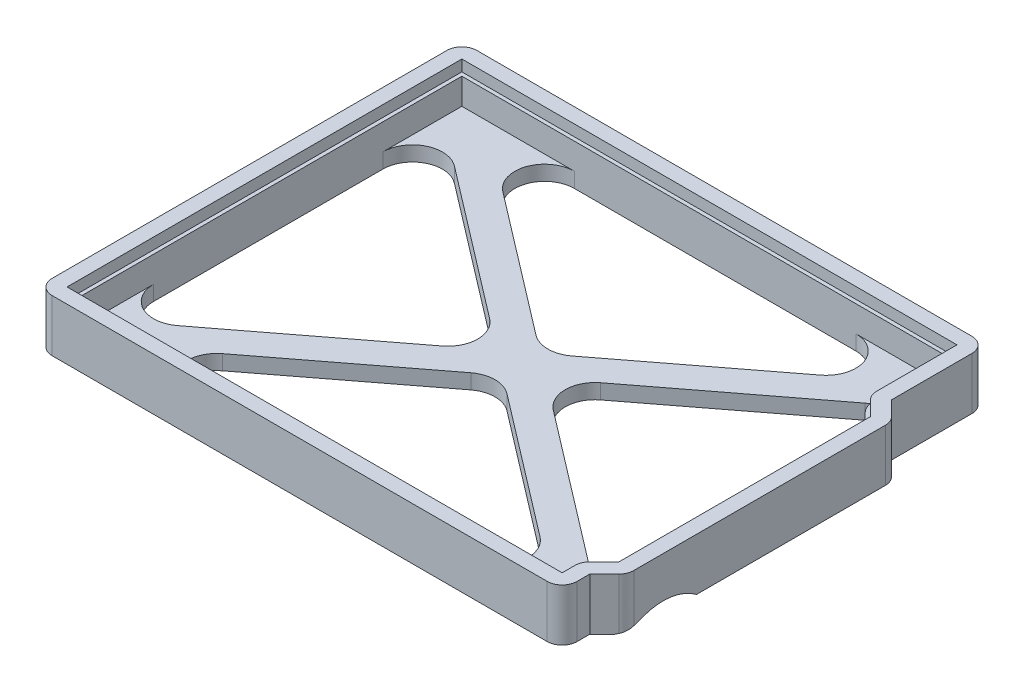
SolidWorks part; units mm, degrees
ref_plane "Спереди" through (0, 0, 0) normal (0, 0, 1) x (1, 0, 0)
ref_plane "Сверху" through (0, 0, 0) normal (0, 1, 0) x (1, 0, 0)
ref_plane "Справа" through (0, 0, 0) normal (1, 0, 0) x (0, 0, -1)
sketch "Эскиз1" plane through (0, 0, 0) normal (0, 1, 0) x (1, 0, 0)
  line L1 (-34.5, -26.5) -> (31.96, -26.5)
  line L2 (-34.5, -26.5) -> (-34.5, 26.5)
  line L3 (-34.5, 26.5) -> (31.96, 26.5)
  line L4 (34.5, -21.42) -> (34.5, 12.346)
  line L10 (-34, -26) -> (-34, 26)
  line L11 (31.96, 14.886) -> (31.96, 26.5)
  line L13 (-36.5, -28.5) -> (33.96, -28.5)
  line L14 (-36.5, -28.5) -> (-36.5, 28.5)
  line L17 (-21.3217, 18.8226) -> (-2.4298, 4.3758)
  line L21 (21.3217, -18.8226) -> (2.4298, -4.3758)
  line L25 (-21.3217, -18.8226) -> (-2.4298, -4.3758)
  line L29 (21.3217, 18.8226) -> (2.4298, 4.3758)
  line L30 (-7.4476, -3.1774) -> (-27.5702, -18.5653)
  line L31 (-7.4476, 3.1774) -> (-27.5702, 18.5653)
  line L32 (7.4476, -3.1774) -> (27.5702, -18.5653)
  line L33 (7.4476, 3.1774) -> (27.5702, 18.5653)
  line L34 (31.96, 14.886) -> (34.5, 12.346)
  line L36 (31.96, -23.96) -> (34.5, -21.42)
  line L37 (31.96, -23.96) -> (31.96, -26.5)
  line L40 (31.46, 14.886) -> (31.46, 26)
  line L41 (31.96, 28.5) -> (33.96, 28.5)
  line L42 (31.6064, 14.5324) -> (34, 12.1389)
  line L43 (31.6064, 14.5324) -> (31.46, 14.6789)
  line L44 (31.46, 14.6789) -> (31.46, 14.886)
  line L45 (31.46, -26) -> (-34, -26)
  line L46 (31.46, -23.96) -> (31.46, -26)
  line L47 (34, -21.2129) -> (34, 12.1389)
  line L48 (31.6064, -23.6064) -> (34, -21.2129)
  line L49 (31.6064, -23.6064) -> (31.46, -23.7529)
  line L50 (31.46, -23.7529) -> (31.46, -23.96)
  line L51 (31.46, 26) -> (-34, 26)
  line L52 (33.96, 28.5) -> (33.96, 15.7144)
  line L53 (31.96, 28.5) -> (-36.5, 28.5)
  line L54 (33.96, 15.7144) -> (36.5, 13.1744)
  line L55 (36.5, 13.1744) -> (36.5, -22.2484)
  line L57 (33.96, -26.5) -> (33.96, -24.7884)
  line L59 (33.96, -24.7884) -> (36.5, -22.2484)
  line L60 (33.96, -26.5) -> (33.96, -28.5)
  arc A0 (-27.5702, 18.5653) -> (-34, 15.3879) centre (-30, 15.3879) ccw
  arc A1 (-7.4476, -3.1774) -> (-7.4476, 3.1774) centre (-9.8774, 0) ccw
  arc A2 (-34, -15.3879) -> (-27.5702, -18.5653) centre (-30, -15.3879) ccw
  arc A3 (-21.3217, -18.8226) -> (-18.8919, -26) centre (-18.8919, -22) ccw
  arc A4 (18.8919, -26) -> (21.3217, -18.8226) centre (18.8919, -22) ccw
  arc A5 (2.4298, -4.3758) -> (-2.4298, -4.3758) centre (0, -7.5533) ccw
  arc A6 (7.4476, 3.1774) -> (7.4476, -3.1774) centre (9.8774, 0) ccw
  arc A7 (27.5702, -18.5653) -> (34, -15.3879) centre (30, -15.3879) ccw
  arc A8 (31.46, 19.1119) -> (27.5702, 18.5653) centre (30, 15.3879) ccw
  arc A9 (21.3217, 18.8226) -> (18.8919, 26) centre (18.8919, 22) ccw
  arc A10 (-18.8919, 26) -> (-21.3217, 18.8226) centre (-18.8919, 22) ccw
  arc A11 (-2.4298, 4.3758) -> (2.4298, 4.3758) centre (0, 7.5533) ccw
  point P0 (0, 0)
  point P6 (0, 0)
  point P11 (0, 0)
extrude "Бобышка-Вытянуть1" add sketch "Эскиз1" along normal blind 2
sketch "Эскиз5" plane through (0, 0, 0) normal (0, 1, 0) x (1, 0, 0)
  line L1 (-34.5, -26.5) -> (31.96, -26.5)
  line L2 (-34.5, -26.5) -> (-34.5, 26.5)
  line L3 (-34.5, 26.5) -> (31.96, 26.5)
  line L4 (34.5, -21.42) -> (34.5, 12.346)
  line L10 (-34, -26) -> (-34, 26)
  line L11 (31.96, 14.886) -> (31.96, 26.5)
  line L13 (-36.5, -28.5) -> (33.96, -28.5)
  line L14 (-36.5, -28.5) -> (-36.5, 28.5)
  line L17 (-21.3217, 18.8226) -> (-2.4298, 4.3758)
  line L21 (21.3217, -18.8226) -> (2.4298, -4.3758)
  line L25 (-21.3217, -18.8226) -> (-2.4298, -4.3758)
  line L29 (21.3217, 18.8226) -> (2.4298, 4.3758)
  line L30 (-7.4476, -3.1774) -> (-27.5702, -18.5653)
  line L31 (-7.4476, 3.1774) -> (-27.5702, 18.5653)
  line L32 (7.4476, -3.1774) -> (27.5702, -18.5653)
  line L33 (7.4476, 3.1774) -> (27.5702, 18.5653)
  line L34 (31.96, 14.886) -> (34.5, 12.346)
  line L36 (31.96, -23.96) -> (34.5, -21.42)
  line L37 (31.96, -23.96) -> (31.96, -26.5)
  line L40 (31.46, 14.886) -> (31.46, 26)
  line L41 (31.96, 28.5) -> (33.96, 28.5)
  line L42 (31.6064, 14.5324) -> (34, 12.1389)
  line L43 (31.6064, 14.5324) -> (31.46, 14.6789)
  line L44 (31.46, 14.6789) -> (31.46, 14.886)
  line L45 (31.46, -26) -> (-34, -26)
  line L46 (31.46, -23.96) -> (31.46, -26)
  line L47 (34, -21.2129) -> (34, 12.1389)
  line L48 (31.6064, -23.6064) -> (34, -21.2129)
  line L49 (31.6064, -23.6064) -> (31.46, -23.7529)
  line L50 (31.46, -23.7529) -> (31.46, -23.96)
  line L51 (31.46, 26) -> (-34, 26)
  line L52 (33.96, 28.5) -> (33.96, 15.7144)
  line L53 (31.96, 28.5) -> (-36.5, 28.5)
  line L54 (33.96, 15.7144) -> (36.5, 13.1744)
  line L55 (36.5, 13.1744) -> (36.5, -22.2484)
  line L57 (33.96, -26.5) -> (33.96, -24.7884)
  line L59 (33.96, -24.7884) -> (36.5, -22.2484)
  line L60 (33.96, -26.5) -> (33.96, -28.5)
  arc A0 (-27.5702, 18.5653) -> (-34, 15.3879) centre (-30, 15.3879) ccw
  arc A1 (-7.4476, -3.1774) -> (-7.4476, 3.1774) centre (-9.8774, 0) ccw
  arc A2 (-34, -15.3879) -> (-27.5702, -18.5653) centre (-30, -15.3879) ccw
  arc A3 (-21.3217, -18.8226) -> (-18.8919, -26) centre (-18.8919, -22) ccw
  arc A4 (18.8919, -26) -> (21.3217, -18.8226) centre (18.8919, -22) ccw
  arc A5 (2.4298, -4.3758) -> (-2.4298, -4.3758) centre (0, -7.5533) ccw
  arc A6 (7.4476, 3.1774) -> (7.4476, -3.1774) centre (9.8774, 0) ccw
  arc A7 (27.5702, -18.5653) -> (34, -15.3879) centre (30, -15.3879) ccw
  arc A8 (31.46, 19.1119) -> (27.5702, 18.5653) centre (30, 15.3879) ccw
  arc A9 (21.3217, 18.8226) -> (18.8919, 26) centre (18.8919, 22) ccw
  arc A10 (-18.8919, 26) -> (-21.3217, 18.8226) centre (-18.8919, 22) ccw
  arc A11 (-2.4298, 4.3758) -> (2.4298, 4.3758) centre (0, 7.5533) ccw
  point P0 (0, 0)
  point P6 (0, 0)
  point P11 (0, 0)
sketch "Эскиз6" plane through (0, 0, 0) normal (0, 1, 0) x (1, 0, 0)
  line L1 (-34.5, -26.5) -> (31.96, -26.5)
  line L2 (-34.5, -26.5) -> (-34.5, 26.5)
  line L3 (-34.5, 26.5) -> (31.96, 26.5)
  line L4 (34.5, -21.42) -> (34.5, 12.346)
  line L10 (-34, -26) -> (-34, 26)
  line L11 (31.96, 14.886) -> (31.96, 26.5)
  line L13 (-36.5, -28.5) -> (33.96, -28.5)
  line L14 (-36.5, -28.5) -> (-36.5, 28.5)
  line L17 (-21.3217, 18.8226) -> (-2.4298, 4.3758)
  line L21 (21.3217, -18.8226) -> (2.4298, -4.3758)
  line L25 (-21.3217, -18.8226) -> (-2.4298, -4.3758)
  line L29 (21.3217, 18.8226) -> (2.4298, 4.3758)
  line L30 (-7.4476, -3.1774) -> (-27.5702, -18.5653)
  line L31 (-7.4476, 3.1774) -> (-27.5702, 18.5653)
  line L32 (7.4476, -3.1774) -> (27.5702, -18.5653)
  line L33 (7.4476, 3.1774) -> (27.5702, 18.5653)
  line L34 (31.96, 14.886) -> (34.5, 12.346)
  line L36 (31.96, -23.96) -> (34.5, -21.42)
  line L37 (31.96, -23.96) -> (31.96, -26.5)
  line L40 (31.46, 14.886) -> (31.46, 26)
  line L41 (31.96, 28.5) -> (33.96, 28.5)
  line L42 (31.6064, 14.5324) -> (34, 12.1389)
  line L43 (31.6064, 14.5324) -> (31.46, 14.6789)
  line L44 (31.46, 14.6789) -> (31.46, 14.886)
  line L45 (31.46, -26) -> (-34, -26)
  line L46 (31.46, -23.96) -> (31.46, -26)
  line L47 (34, -21.2129) -> (34, 12.1389)
  line L48 (31.6064, -23.6064) -> (34, -21.2129)
  line L49 (31.6064, -23.6064) -> (31.46, -23.7529)
  line L50 (31.46, -23.7529) -> (31.46, -23.96)
  line L51 (31.46, 26) -> (-34, 26)
  line L52 (33.96, 28.5) -> (33.96, 15.7144)
  line L53 (31.96, 28.5) -> (-36.5, 28.5)
  line L54 (33.96, 15.7144) -> (36.5, 13.1744)
  line L55 (36.5, 13.1744) -> (36.5, -22.2484)
  line L57 (33.96, -26.5) -> (33.96, -24.7884)
  line L59 (33.96, -24.7884) -> (36.5, -22.2484)
  line L60 (33.96, -26.5) -> (33.96, -28.5)
  arc A0 (-27.5702, 18.5653) -> (-34, 15.3879) centre (-30, 15.3879) ccw
  arc A1 (-7.4476, -3.1774) -> (-7.4476, 3.1774) centre (-9.8774, 0) ccw
  arc A2 (-34, -15.3879) -> (-27.5702, -18.5653) centre (-30, -15.3879) ccw
  arc A3 (-21.3217, -18.8226) -> (-18.8919, -26) centre (-18.8919, -22) ccw
  arc A4 (18.8919, -26) -> (21.3217, -18.8226) centre (18.8919, -22) ccw
  arc A5 (2.4298, -4.3758) -> (-2.4298, -4.3758) centre (0, -7.5533) ccw
  arc A6 (7.4476, 3.1774) -> (7.4476, -3.1774) centre (9.8774, 0) ccw
  arc A7 (27.5702, -18.5653) -> (34, -15.3879) centre (30, -15.3879) ccw
  arc A8 (31.46, 19.1119) -> (27.5702, 18.5653) centre (30, 15.3879) ccw
  arc A9 (21.3217, 18.8226) -> (18.8919, 26) centre (18.8919, 22) ccw
  arc A10 (-18.8919, 26) -> (-21.3217, 18.8226) centre (-18.8919, 22) ccw
  arc A11 (-2.4298, 4.3758) -> (2.4298, 4.3758) centre (0, 7.5533) ccw
  point P0 (0, 0)
  point P6 (0, 0)
  point P11 (0, 0)
extrude "Бобышка-Вытянуть2" add sketch "Эскиз5" along normal blind 7 contours L60 L57 L59 L55 L54 L52 L41 L53 L14 L13 L36 L37 L1 L2 L3 L11 L34 L4
extrude "Бобышка-Вытянуть3" add sketch "Эскиз6" along normal blind 5.5 contours L37 L36 L4 L34 L11 L3 L2 L1 L51 L40 L44 L43 L42 L47 L48 L49 L50 L46 L45 L10
fillet "Скругление1" radius 2 8 edges at (-36.5, 3.5, 28.5) (-36.5, 3.5, -28.5) (31.96, 6.25, 23.96) (31.96, 6.25, -14.886) (33.96, 3.5, -28.5) (36.5, 3.5, -13.1744) (36.5, 3.5, 22.2484) (33.96, 3.5, 28.5)
fillet "Скругление2" radius 2.5 2 edges at (31.46, 3.75, 23.7529) (31.46, 2.75, -14.6789)
sketch "Эскиз4" plane through (36.5, 0, 0) normal (1, 0, 0) x (0, 0, -1)
  line L0 (-23.0809, 0) -> (-19.963, 1.084)
  line L1 (-23.0809, 0) -> (-13, 0)
  arc A0 (-13, 0) -> (-19.963, 1.084) centre (-17.5, -6) ccw
extrude "Вырез-Вытянуть1" cut sketch "Эскиз4" against normal blind 2.2
mirror "Зеркальное отражение1" about plane through (0, 0, 0) normal (1, 0, 0) of "Вырез-Вытянуть1"
sketch "Эскиз7" plane through (0, 0, 0) normal (0, -1, 0) x (1, 0, 0)
  circle A0 centre (14.2436, 9.9372) radius 0.5
  circle A1 centre (23.6, -26.1) radius 0.5
  circle A2 centre (-14.2436, 9.9372) radius 0.5
  circle A3 centre (-23.6, -26.1) radius 0.5021
extrude "Вырез-Вытянуть2" cut sketch "Эскиз7" against normal blind 0.5
